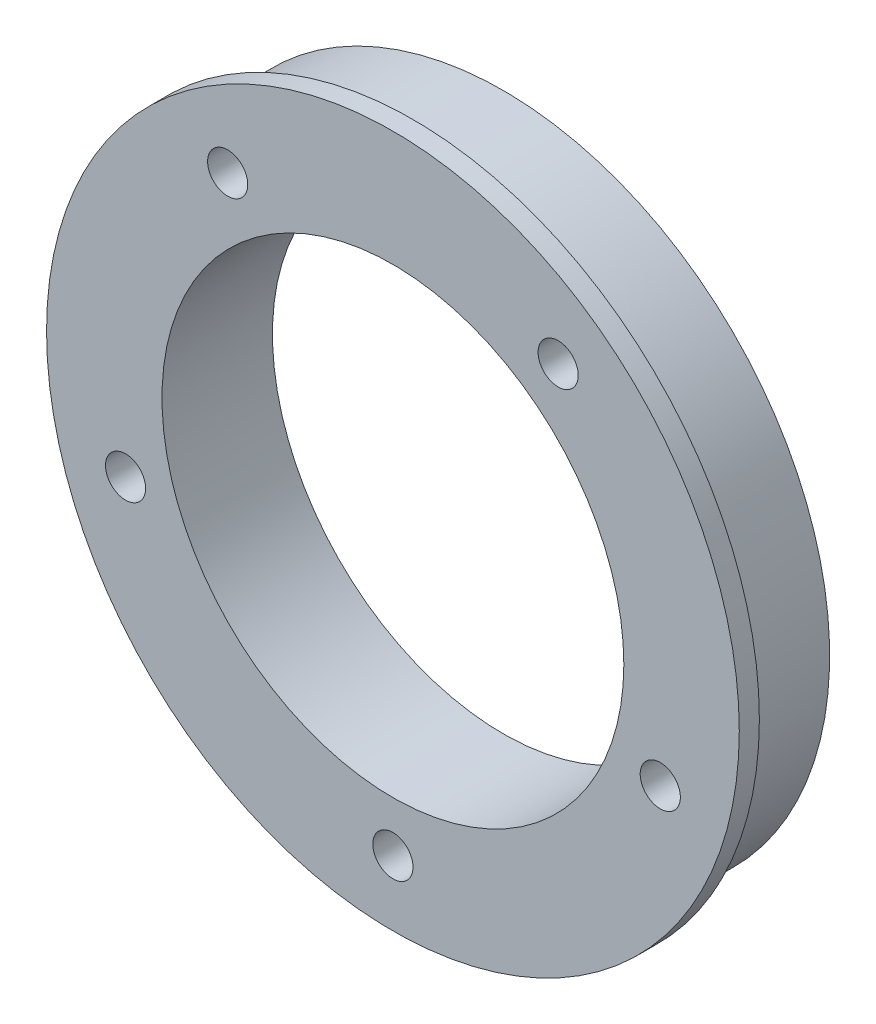
SolidWorks part; units mm, degrees
ref_plane "前视基准面" through (0, 0, 0) normal (0, 0, 1) x (1, 0, 0)
ref_plane "上视基准面" through (0, 0, 0) normal (0, 1, 0) x (1, 0, 0)
ref_plane "右视基准面" through (0, 0, 0) normal (1, 0, 0) x (0, 0, -1)
sketch "草图1" plane through (0, 0, 0) normal (0, 0, 1) x (1, 0, 0)
  circle A0 centre (0, 0) radius 23
  circle A1 centre (0, 0) radius 34.5
  circle A2 centre (0, 0) radius 28 construction
  circle A3 centre (0, -28) radius 2
  circle A4 centre (-26.6296, -8.6525) radius 2
  circle A5 centre (-16.458, 22.6525) radius 2
  circle A6 centre (16.458, 22.6525) radius 2
  circle A7 centre (26.6296, -8.6525) radius 2
  circle A8 centre (0, 0) radius 31.4118
  dimension "D1" = 46
  dimension "D2" = 69
  dimension "D3" = 56
  dimension "D4" = 4
  dimension "D6" = 62.8235
  dimension "D5" = 5
extrude "凸台-拉伸1" add sketch "草图1" along normal blind 11 contours A1
sketch "草图2" plane through (0, 0, 0) normal (0, 0, -1) x (-1, 0, 0)
  circle A0 centre (0, 0) radius 32.5
  circle A1 centre (0, 0) radius 34.5
  dimension "D1" = 65
extrude "切除-拉伸1" cut sketch "草图2" against normal blind 9
